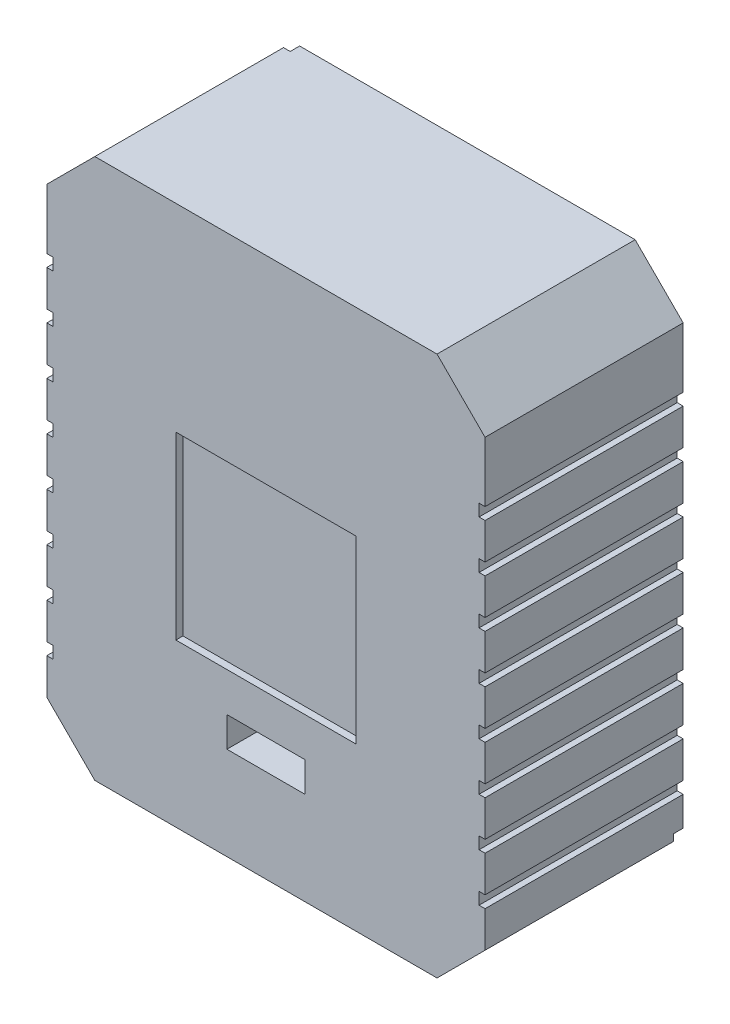
SolidWorks part; units mm, degrees
ref_plane "Front Plane" through (0, 0, 0) normal (0, 0, 1) x (1, 0, 0)
ref_plane "Top Plane" through (0, 0, 0) normal (0, 1, 0) x (1, 0, 0)
ref_plane "Right Plane" through (0, 0, 0) normal (1, 0, 0) x (0, 0, -1)
sketch "Sketch1" plane through (0, 0, 0) normal (0, 0, 1) x (1, 0, 0)
  line L1 (-46.355, -57.15) -> (46.355, -57.15)
  line L2 (-46.355, -57.15) -> (-46.355, 57.15)
  line L3 (-46.355, 57.15) -> (46.355, 57.15)
  line L4 (46.355, -57.15) -> (46.355, 57.15)
  line L5 (-46.355, -57.15) -> (46.355, 57.15) construction
  line L6 (-46.355, 57.15) -> (46.355, -57.15) construction
  point P0 (0, 0)
  dimension "D1" = 92.71
  dimension "D2" = 114.3
extrude "Boss-Extrude1" add sketch "Sketch1" along normal blind 41.91
sketch "Sketch2" plane through (0, 0, 0) normal (0, 0, -1) x (-1, 0, 0)
  line L0 (-46.355, -57.15) -> (-46.355, 57.15) construction
  line L1 (-47.625, -39.37) -> (-45.085, -39.37)
  line L2 (-47.625, -39.37) -> (-47.625, -36.83)
  line L3 (-47.625, -36.83) -> (-45.085, -36.83)
  line L4 (-45.085, -39.37) -> (-45.085, -36.83)
  line L5 (-47.625, -39.37) -> (-45.085, -36.83) construction
  line L6 (-47.625, -36.83) -> (-45.085, -39.37) construction
  line L7 (46.355, 57.15) -> (46.355, -57.15) construction
  line L8 (47.625, -39.37) -> (45.085, -39.37)
  line L9 (47.625, -39.37) -> (47.625, -36.83)
  line L10 (47.625, -36.83) -> (45.085, -36.83)
  line L11 (45.085, -39.37) -> (45.085, -36.83)
  line L12 (47.625, -39.37) -> (45.085, -36.83) construction
  line L13 (47.625, -36.83) -> (45.085, -39.37) construction
  line L14 (-47.625, -26.67) -> (-45.085, -26.67)
  line L15 (-47.625, -29.21) -> (-47.625, -26.67)
  line L16 (-47.625, -29.21) -> (-45.085, -29.21)
  line L17 (-45.085, -29.21) -> (-45.085, -26.67)
  line L18 (47.625, -29.21) -> (47.625, -26.67)
  line L19 (47.625, -26.67) -> (45.085, -26.67)
  line L20 (45.085, -29.21) -> (45.085, -26.67)
  line L21 (47.625, -29.21) -> (45.085, -29.21)
  line L22 (-47.625, -16.51) -> (-45.085, -16.51)
  line L23 (-47.625, -19.05) -> (-47.625, -16.51)
  line L24 (-47.625, -19.05) -> (-45.085, -19.05)
  line L25 (-45.085, -19.05) -> (-45.085, -16.51)
  line L26 (47.625, -19.05) -> (47.625, -16.51)
  line L27 (47.625, -16.51) -> (45.085, -16.51)
  line L28 (45.085, -19.05) -> (45.085, -16.51)
  line L29 (47.625, -19.05) -> (45.085, -19.05)
  line L30 (-47.625, -6.35) -> (-45.085, -6.35)
  line L31 (-47.625, -8.89) -> (-47.625, -6.35)
  line L32 (-47.625, -8.89) -> (-45.085, -8.89)
  line L33 (-45.085, -8.89) -> (-45.085, -6.35)
  line L34 (47.625, -8.89) -> (47.625, -6.35)
  line L35 (47.625, -6.35) -> (45.085, -6.35)
  line L36 (45.085, -8.89) -> (45.085, -6.35)
  line L37 (47.625, -8.89) -> (45.085, -8.89)
  line L38 (-47.625, 3.81) -> (-45.085, 3.81)
  line L39 (-47.625, 1.27) -> (-47.625, 3.81)
  line L40 (-47.625, 1.27) -> (-45.085, 1.27)
  line L41 (-45.085, 1.27) -> (-45.085, 3.81)
  line L42 (47.625, 1.27) -> (47.625, 3.81)
  line L43 (47.625, 3.81) -> (45.085, 3.81)
  line L44 (45.085, 1.27) -> (45.085, 3.81)
  line L45 (47.625, 1.27) -> (45.085, 1.27)
  line L46 (-47.625, 13.97) -> (-45.085, 13.97)
  line L47 (-47.625, 11.43) -> (-47.625, 13.97)
  line L48 (-47.625, 11.43) -> (-45.085, 11.43)
  line L49 (-45.085, 11.43) -> (-45.085, 13.97)
  line L50 (47.625, 11.43) -> (47.625, 13.97)
  line L51 (47.625, 13.97) -> (45.085, 13.97)
  line L52 (45.085, 11.43) -> (45.085, 13.97)
  line L53 (47.625, 11.43) -> (45.085, 11.43)
  line L54 (-47.625, 24.13) -> (-45.085, 24.13)
  line L55 (-47.625, 21.59) -> (-47.625, 24.13)
  line L56 (-47.625, 21.59) -> (-45.085, 21.59)
  line L57 (-45.085, 21.59) -> (-45.085, 24.13)
  line L58 (47.625, 21.59) -> (47.625, 24.13)
  line L59 (47.625, 24.13) -> (45.085, 24.13)
  line L60 (45.085, 21.59) -> (45.085, 24.13)
  line L61 (47.625, 21.59) -> (45.085, 21.59)
  line L62 (46.355, -57.15) -> (-46.355, -57.15) construction
  line L63 (-47.625, 34.29) -> (-45.085, 34.29)
  line L64 (-47.625, 31.75) -> (-47.625, 34.29)
  line L65 (-47.625, 31.75) -> (-45.085, 31.75)
  line L66 (-45.085, 31.75) -> (-45.085, 34.29)
  line L67 (47.625, 34.29) -> (45.085, 34.29)
  line L68 (45.085, 31.75) -> (45.085, 34.29)
  line L69 (47.625, 31.75) -> (45.085, 31.75)
  line L70 (47.625, 31.75) -> (47.625, 34.29)
  point P0 (-46.355, -38.1)
  point P7 (46.355, -38.1)
  dimension "D1" = 2.54
  dimension "D2" = 2.54
  dimension "D3" = 17.78
  dimension "D4" = 2.54
  dimension "D6" = 17.78
  dimension "D5" = 7
  dimension "D7" = 2
extrude "Cut-Extrude1" cut sketch "Sketch2" against normal through all
chamfer "Chamfer1" distance 10.16 angle 45 4 edges at (46.355, 57.15, 20.955) (46.355, -57.15, 20.955) (-46.355, -57.15, 20.955) (-46.355, 57.15, 20.955)
sketch "Sketch3" plane through (0, 0, 0) normal (0, 0, -1) x (-1, 0, 0)
  line L0 (46.355, -39.37) -> (46.355, -46.99) construction
  line L1 (-46.355, -46.99) -> (-46.355, -39.37) construction
  line L2 (36.195, -57.15) -> (-36.195, -57.15) construction
  line L3 (-36.195, 57.15) -> (36.195, 57.15) construction
  line L4 (-46.355, 24.13) -> (-46.355, 31.75) construction
  line L5 (46.355, 46.99) -> (46.355, 34.29) construction
  circle A0 centre (-27.305, -53.65) radius 1.75
  circle A1 centre (-27.305, 53.65) radius 1.75
  circle A2 centre (27.305, 53.65) radius 1.75
  circle A3 centre (27.305, -53.65) radius 1.75
  dimension "D1" = 3.5
  dimension "D2" = 3.5
  dimension "D3" = 3.5
  dimension "D4" = 3.5
  dimension "D5" = 19.05
  dimension "D6" = 19.05
  dimension "D7" = 3.5
  dimension "D8" = 3.5
  dimension "D9" = 3.5
  dimension "D11" = 19.05
  dimension "D12" = 19.05
  dimension "D10" = 3.5
extrude "Cut-Extrude2" cut sketch "Sketch3" against normal blind 25.4
sketch "Sketch4" plane through (0, 0, 0) normal (0, 0, -1) x (-1, 0, 0)
  line L0 (-36.195, 57.15) -> (36.195, 57.15) construction
  line L1 (-39.355, -50.15) -> (39.355, -50.15)
  line L2 (-39.355, -50.15) -> (-39.355, 50.15)
  line L3 (-39.355, 50.15) -> (39.355, 50.15)
  line L4 (39.355, -50.15) -> (39.355, 50.15)
  line L5 (-39.355, -50.15) -> (39.355, 50.15) construction
  line L6 (-39.355, 50.15) -> (39.355, -50.15) construction
  line L7 (-46.355, 13.97) -> (-46.355, 21.59) construction
  point P0 (0, 0)
  dimension "D1" = 7
  dimension "D2" = 7
extrude "Cut-Extrude3" cut sketch "Sketch4" against normal blind 35.56
sketch "Sketch6" plane through (0, 0, 41.91) normal (0, 0, 1) x (1, 0, 0)
  line L0 (-36.195, -57.15) -> (36.195, -57.15) construction
  line L10 (-8.255, -37.465) -> (8.255, -37.465)
  line L11 (-8.255, -37.465) -> (-8.255, -31.115)
  line L12 (-8.255, -31.115) -> (8.255, -31.115)
  line L13 (8.255, -37.465) -> (8.255, -31.115)
  line L14 (-8.255, -37.465) -> (8.255, -31.115) construction
  line L15 (-8.255, -31.115) -> (8.255, -37.465) construction
  point P7 (0, -34.29)
  dimension "D5" = 6.35
  dimension "D7" = 16.51
  dimension "D8" = 22.86
extrude "Cut-Extrude5" cut sketch "Sketch6" against normal through all
sketch "Sketch7" plane through (0, 0, 0) normal (0, 0, -1) x (-1, 0, 0)
  line L2 (40.5679, 51.3629) -> (46.355, 45.5758)
  line L3 (46.355, 46.99) -> (46.355, 34.29) construction
  line L4 (46.355, 45.5758) -> (46.355, 46.99)
  line L5 (46.355, 46.99) -> (36.195, 57.15)
  line L6 (40.5679, 51.3629) -> (34.7808, 57.15)
  line L7 (-36.195, 57.15) -> (36.195, 57.15) construction
  line L8 (34.7808, 57.15) -> (36.195, 57.15)
  line L10 (-40.5679, -51.3629) -> (-46.355, -45.5758)
  line L11 (-46.355, -46.99) -> (-46.355, -39.37) construction
  line L12 (-46.355, -45.5758) -> (-46.355, -46.99)
  line L13 (-46.355, -46.99) -> (-36.195, -57.15)
  line L14 (-40.5679, -51.3629) -> (-34.7808, -57.15)
  line L15 (36.195, -57.15) -> (-36.195, -57.15) construction
  line L16 (-34.7808, -57.15) -> (-36.195, -57.15)
extrude "Cut-Extrude6" cut sketch "Sketch7" against normal blind 2
sketch "Sketch8" plane through (0, 0, 41.91) normal (0, 0, 1) x (1, 0, 0)
  line L3 (19.05, -22.86) -> (19.05, 15.24) construction
  line L4 (-19.05, -22.86) -> (19.05, -22.86)
  line L5 (-19.05, -22.86) -> (-19.05, 15.24)
  line L6 (-19.05, 15.24) -> (19.05, 15.24)
  line L7 (19.05, -22.86) -> (19.05, 15.24)
  line L8 (-19.05, -22.86) -> (19.05, 15.24) construction
  line L9 (-19.05, 15.24) -> (19.05, -22.86) construction
  point P6 (0, -3.81)
extrude "Cut-Extrude7" cut sketch "Sketch8" against normal blind 1.5
